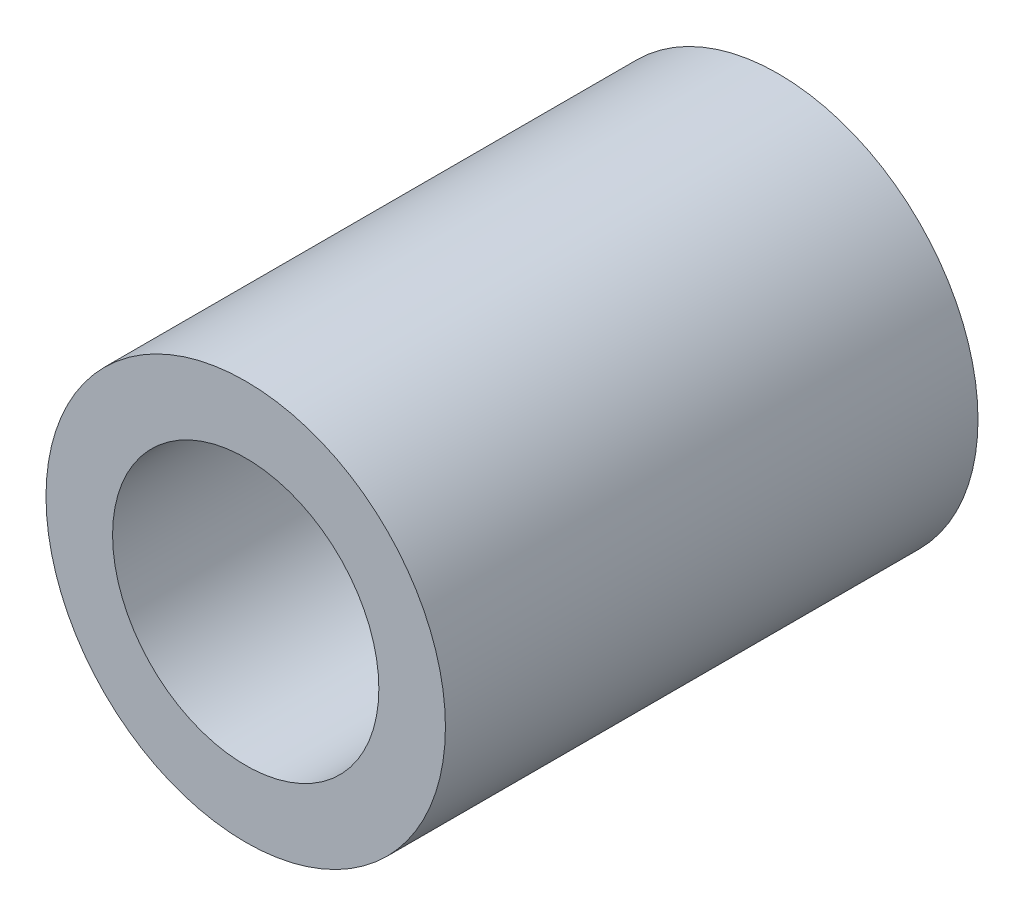
SolidWorks part; units mm, degrees
ref_plane "Plan de face" through (0, 0, 0) normal (0, 0, 1) x (1, 0, 0)
ref_plane "Plan de dessus" through (0, 0, 0) normal (0, 1, 0) x (1, 0, 0)
ref_plane "Plan de droite" through (0, 0, 0) normal (1, 0, 0) x (0, 0, -1)
sketch "Esquisse1" plane through (0, 0, 0) normal (0, 0, 1) x (1, 0, 0)
  circle A0 centre (0, 0) radius 4
  circle A1 centre (0, 0) radius 6
  dimension "D1" = 8
  dimension "D2" = 12
extrude "Extrusion1" add sketch "Esquisse1" along normal blind 16
